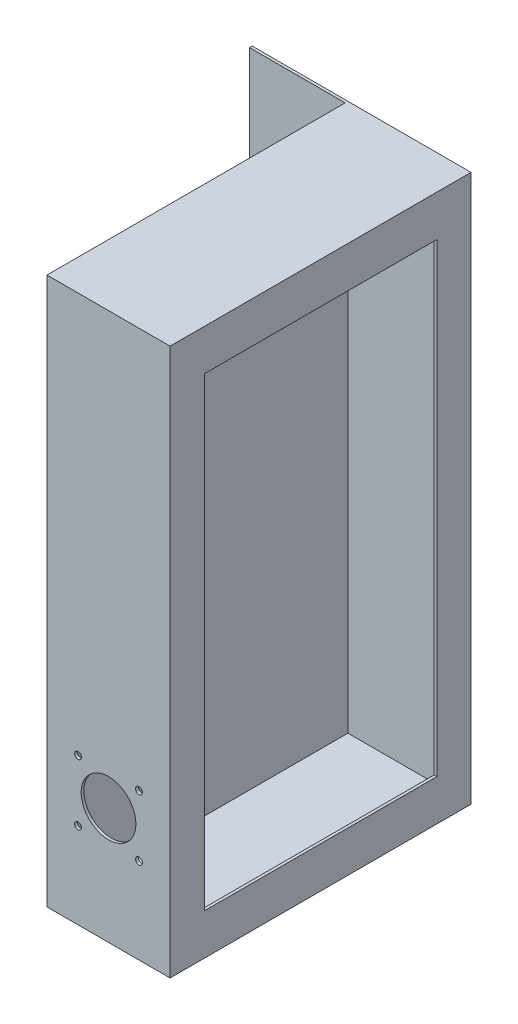
SolidWorks part; units mm, degrees
ref_plane "Front Plane" through (0, 0, 0) normal (0, 0, 1) x (1, 0, 0)
ref_plane "Top Plane" through (0, 0, 0) normal (0, 1, 0) x (1, 0, 0)
ref_plane "Right Plane" through (0, 0, 0) normal (1, 0, 0) x (0, 0, -1)
sketch "Sketch1" plane through (0, 0, 0) normal (0, 0, 1) x (1, 0, 0)
  line L1 (-45, 200) -> (45, 200)
  line L2 (-45, 200) -> (-45, -200)
  line L3 (-45, -200) -> (45, -200)
  line L4 (45, 200) -> (45, -200)
  line L5 (-45, 200) -> (45, -200) construction
  line L6 (-45, -200) -> (45, 200) construction
  point P0 (0, 0)
  dimension "D1" = 90
  dimension "D2" = 400
extrude "Boss-Extrude1" add sketch "Sketch1" along normal mid plane 220
shell "Shell1" thickness 2
sketch "Sketch2" plane through (45, 0, 0) normal (1, 0, 0) x (0, 0, -1)
  line L1 (-85, 170) -> (85, 170)
  line L2 (-85, 170) -> (-85, -170)
  line L3 (-85, -170) -> (85, -170)
  line L4 (85, 170) -> (85, -170)
  line L5 (-85, 170) -> (85, -170) construction
  line L6 (-85, -170) -> (85, 170) construction
  point P0 (0, 0)
  dimension "D1" = 170
  dimension "D2" = 340
extrude "Cut-Extrude2" cut sketch "Sketch2" against normal up to next
sketch "Sketch3" plane through (0, 0, 110) normal (0, 0, 1) x (1, 0, 0)
  line L0 (-1163.1443, 105.7417) -> (-1013.2205, 105.7417) construction
  line L1 (-45, 174.8012) -> (45, 174.8012) construction
  line L2 (665.1147, 743.938) -> (2665.1147, 743.938) construction
sketch "Sketch4" plane through (0, 0, 110) normal (0, 0, 1) x (1, 0, 0)
  line L0 (-293, -173.4531) -> (-203, -173.4531) construction
sketch "Sketch5" plane through (0, 0, 110) normal (0, 0, 1) x (1, 0, 0)
  line L0 (-45, -200) -> (45, -200) construction
  line L2 (-22.275, -92.725) -> (22.275, -92.725) construction
  line L3 (-22.275, -92.725) -> (-22.275, -137.275) construction
  line L4 (-22.275, -137.275) -> (22.275, -137.275) construction
  line L5 (22.275, -92.725) -> (22.275, -137.275) construction
  line L6 (-22.275, -92.725) -> (22.275, -137.275) construction
  line L7 (-22.275, -137.275) -> (22.275, -92.725) construction
  circle A0 centre (0, -115) radius 20
  circle A1 centre (-22.275, -92.725) radius 2.5
  circle A2 centre (22.275, -92.725) radius 2.5
  circle A3 centre (-22.275, -137.275) radius 2.5
  circle A4 centre (22.275, -137.275) radius 2.5
  dimension "D1" = 40
  dimension "D5" = 5
  dimension "D2" = 85
  dimension "D3" = 44.55
  dimension "D4" = 44.55
extrude "Cut-Extrude3" cut sketch "Sketch5" against normal up to next
sketch "Sketch6" plane through (0, 0, -110) normal (0, 0, -1) x (-1, 0, 0)
  line L0 (45, -200) -> (-45, -200) construction
  line L1 (45, 200) -> (115, 200)
  line L2 (45, 200) -> (45, -200)
  line L3 (45, -200) -> (115, -200)
  line L4 (115, 200) -> (115, -200)
  line L5 (-45, -200) -> (-45, 200) construction
  dimension "D1" = 160
extrude "Boss-Extrude2" add sketch "Sketch6" against normal blind 2
